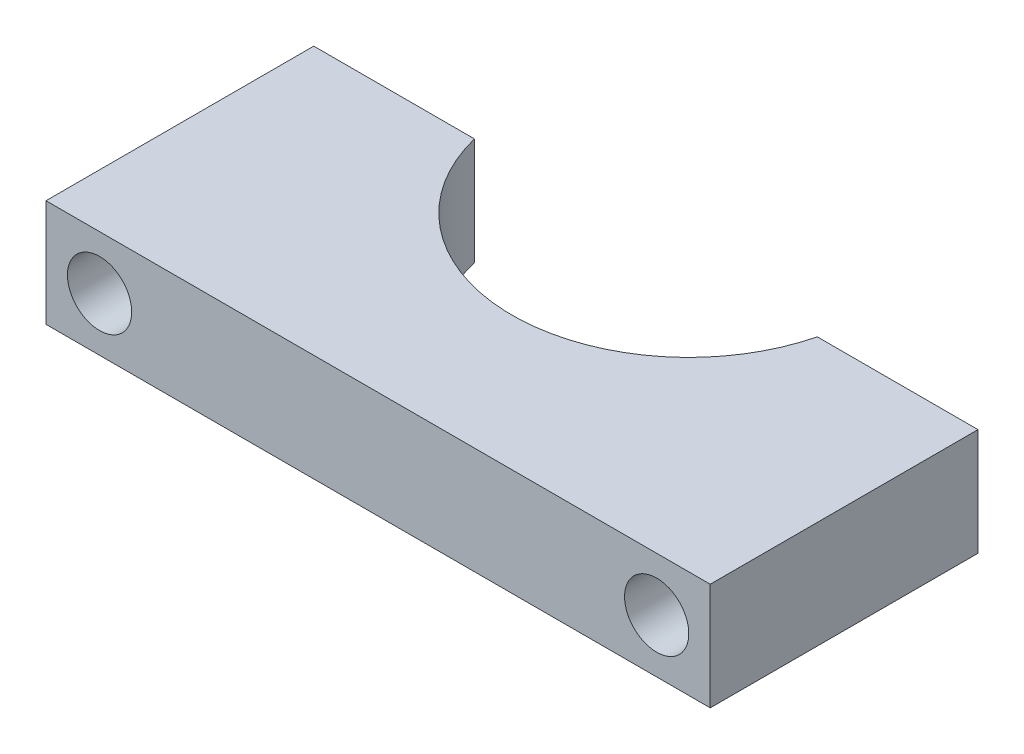
SolidWorks part; units mm, degrees
material "6061 Alloy"
ref_plane "Front Plane" through (0, 0, 0) normal (0, 0, 1) x (1, 0, 0)
ref_plane "Top Plane" through (0, 0, 0) normal (0, 1, 0) x (1, 0, 0)
ref_plane "Right Plane" through (0, 0, 0) normal (1, 0, 0) x (0, 0, -1)
sketch "Sketch1" plane through (0, 0, 0) normal (0, 1, 0) x (1, 0, 0)
  line L0 (-16.0078, -4) -> (-31.0078, -4)
  line L3 (22, -29) -> (-22, -29)
  line L6 (-31.0078, -4) -> (-31.0078, -29)
  line L7 (-31.0078, -29) -> (-22, -29)
  line L8 (16.0078, -4) -> (31.0078, -4)
  line L9 (31.0078, -4) -> (31.0078, -29)
  line L10 (31.0078, -29) -> (22, -29)
  arc A0 (-16.0078, -4) -> (16.0078, -4) centre (0, 0) ccw
  dimension "D1" = 33
extrude "Boss-Extrude1" add sketch "Sketch1" along normal blind 10
sketch "Sketch2" plane through (0, 0, 4) normal (0, 0, -1) x (-1, 0, 0)
  line L0 (-31.0078, 5) -> (-26.0078, 5) construction
  line L3 (-31.0078, 10) -> (-31.0078, 0) construction
  line L6 (31.0078, 5) -> (26.0078, 5) construction
  line L7 (31.0078, 10) -> (31.0078, 0) construction
  circle A2 centre (-26.0078, 5) radius 3
  circle A3 centre (26.0078, 5) radius 3
extrude "Cut-Extrude1" cut sketch "Sketch2" against normal blind 27
